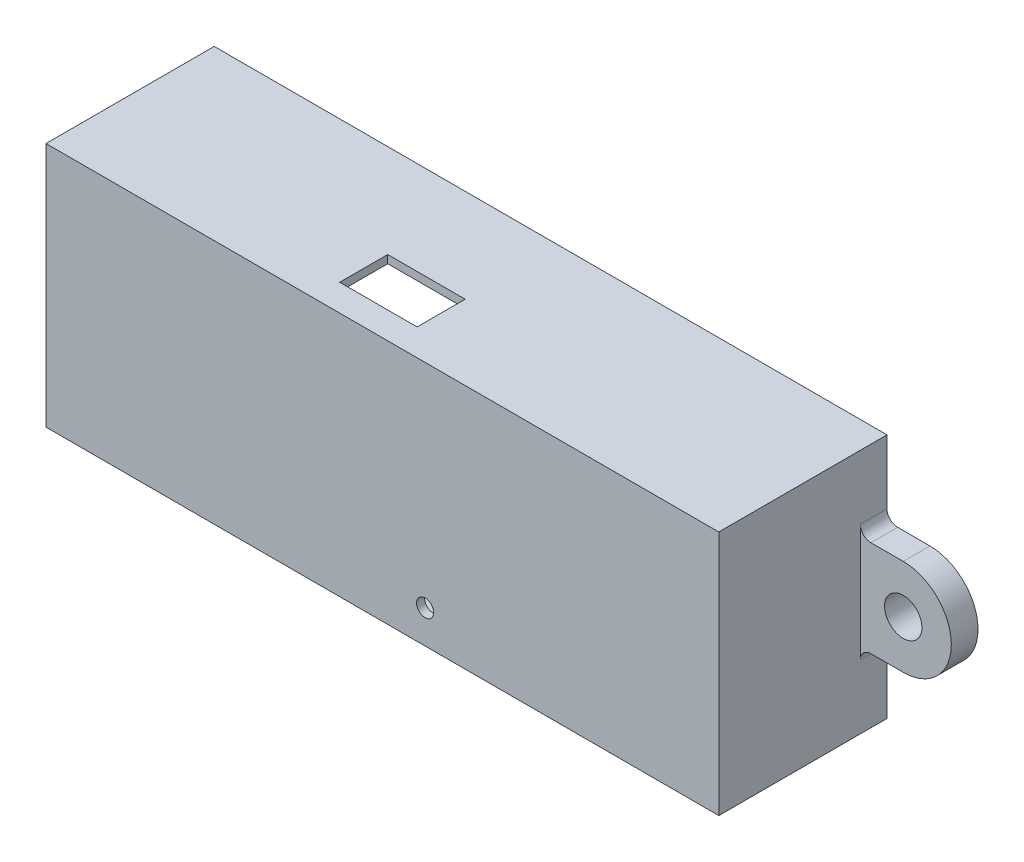
SolidWorks part; units mm, degrees
ref_plane "Спереди" through (0, 0, 0) normal (0, 0, 1) x (1, 0, 0)
ref_plane "Сверху" through (0, 0, 0) normal (0, 1, 0) x (1, 0, 0)
ref_plane "Справа" through (0, 0, 0) normal (1, 0, 0) x (0, 0, -1)
sketch "Эскиз1" plane through (0, 0, 0) normal (0, 0, 1) x (1, 0, 0)
  line L5 (0, 0) -> (123, 0)
  line L6 (0, 0) -> (0, 43)
  line L7 (0, 43) -> (123, 43)
  line L8 (123, 0) -> (123, 43)
  dimension "D1" = 123
  dimension "D2" = 43
extrude "Бобышка-Вытянуть1" add sketch "Эскиз1" along normal blind 1.5
sketch "Эскиз2" plane through (0, 0, 0) normal (0, 0, -1) x (-1, 0, 0)
  line L1 (-124.5, -1.5) -> (1.5, -1.5)
  line L2 (-124.5, -1.5) -> (-124.5, 44.5)
  line L3 (-124.5, 44.5) -> (1.5, 44.5)
  line L4 (1.5, -1.5) -> (1.5, 44.5)
  line L9 (-123, 0) -> (0, 0)
  line L10 (-123, 0) -> (-123, 43)
  line L11 (-123, 43) -> (0, 43)
  line L12 (0, 0) -> (0, 43)
  dimension "D1" = 1.5
  dimension "D2" = 1.5
  dimension "D3" = 1.5
  dimension "D4" = 1.5
extrude "Бобышка-Вытянуть2" add sketch "Эскиз2" along normal blind 30 and the other way blind 1.5
sketch "Эскиз3" plane through (0, 0, -30) normal (0, 0, -1) x (-1, 0, 0)
  line L0 (-124.5, 12.5) -> (-132.54, 12.5)
  line L1 (-124.5, 30.5) -> (-132.54, 30.5)
  line L2 (-134.7332, 21.5) -> (-136.04, 21.5) construction
  line L3 (-124.5, 30.5) -> (-124.5, 12.5)
  line L4 (-123, 21.5) -> (0, 21.5) construction
  line L5 (-123, 43) -> (-123, 0) construction
  line L6 (0, 0) -> (0, 43) construction
  line L7 (-124.5, 44.5) -> (-124.5, -1.5) construction
  arc A0 (-132.54, 12.5) -> (-132.54, 30.5) centre (-132.54, 21.5) cw
  circle A1 centre (-132.54, 21.5) radius 3.5
  dimension "D1" = 7
  dimension "D3" = 9
  dimension "D2" = 9
  dimension "D4" = 8.04
extrude "Бобышка-Вытянуть3" add sketch "Эскиз3" against normal blind 5
ref_plane "Плоскость1" through (61.5, 0, 0) normal (1, 0, 0) x (0, 0, -1)
mirror "Зеркальное отражение1" about plane through (61.5, 0, 0) normal (1, 0, 0) of "Бобышка-Вытянуть3"
ref_plane "Плоскость2" through (123, 43, -30) normal (0, 0, -1) x (-1, 0, 0)
sketch "Эскиз5" plane through (0, 0, 1.5) normal (0, 0, 1) x (1, 0, 0)
  circle A0 centre (69.5, 4.7) radius 1.6
  dimension "D5" = 3.2
  dimension "D6" = 55
  dimension "D7" = 6.2
extrude "Вырез-Вытянуть1" cut sketch "Эскиз5" against normal blind 10
sketch "Эскиз6" plane through (-1.5, 0, 0) normal (-1, 0, 0) x (0, 0, 1)
  line L0 (-20, 17.3) -> (-22.5, 17.3)
  line L6 (-25, 9.65) -> (-25, 16.65)
  line L8 (-20, 8.5) -> (-20, 17.3)
  line L11 (-20, 8.5) -> (-22.5, 8.5)
  line L14 (-22.5, 17.3) -> (-25, 17.3)
  line L15 (-25, 17.3) -> (-25, 16.65)
  line L16 (-25, 9.65) -> (-25, 8.5)
  line L17 (1.5, -1.5) -> (-30, -1.5) construction
  line L18 (-30, -1.5) -> (-30, 12.5) construction
  line L19 (-25, 8.5) -> (-22.5, 8.5)
  dimension "D2" = 8.8
  dimension "D3" = 5
  dimension "D5" = 10
  dimension "D6" = 5
extrude "Вырез-Вытянуть2" cut sketch "Эскиз6" against normal blind 10
sketch "Эскиз7" plane through (0, 44.5, 0) normal (0, 1, 0) x (1, 0, 0)
  line L0 (-1.5, -1.5) -> (-1.5, 30) construction
  line L1 (48.5, 3.5) -> (63, 3.5)
  line L2 (48.5, 3.5) -> (48.5, 12.5)
  line L3 (48.5, 12.5) -> (63, 12.5)
  line L4 (63, 3.5) -> (63, 12.5)
  line L5 (-1.5, -1.5) -> (124.5, -1.5) construction
  dimension "D1" = 14.5
  dimension "D2" = 9
  dimension "D3" = 50
  dimension "D4" = 5
extrude "Вырез-Вытянуть3" cut sketch "Эскиз7" against normal blind 10
fillet "Скругление1" radius 2 4 edges at (124.5, 12.5, -27.5) (124.5, 30.5, -27.5) (-1.5, 30.5, -27.5) (-1.5, 12.5, -27.5)
